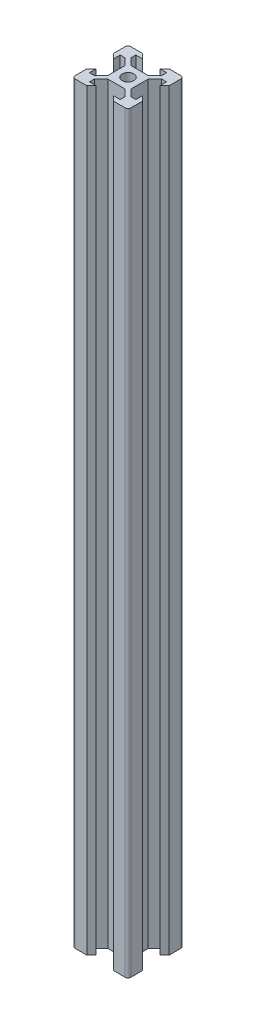
SolidWorks part; units mm, degrees
material "1060 Alloy"
ref_plane "Front Plane" through (0, 0, 0) normal (0, 0, 1) x (1, 0, 0)
ref_plane "Top Plane" through (0, 0, 0) normal (0, 1, 0) x (1, 0, 0)
ref_plane "Right Plane" through (0, 0, 0) normal (1, 0, 0) x (0, 0, -1)
ref_plane "End Plane" through (0, 270, 0) normal (0, 1, 0) x (1, 0, 0)
sketch "MasterLayoutSketch" plane through (0, 0, 0) normal (0, 1, 0) x (1, 0, 0)
  line L0 (-8.325, 3.1) -> (-8.325, 5.5)
  line L1 (-10, -10) -> (10, -10) construction
  line L2 (-10, -10) -> (-10, 10) construction
  line L3 (-10, 10) -> (10, 10) construction
  line L4 (10, -10) -> (10, 10) construction
  line L5 (-10, -10) -> (10, 10) construction
  line L6 (-10, 10) -> (10, -10) construction
  line L7 (-4.775, 10) -> (-3.1, 8.325)
  line L10 (-8.325, 5.5) -> (-6.5607, 5.5)
  line L11 (-10, 4.775) -> (-8.325, 3.1)
  line L12 (-5.5, 8.325) -> (-5.5, 6.5607)
  line L13 (-3.1, 8.325) -> (-5.5, 8.325)
  line L14 (-10, 10) -> (-10, 4.775)
  line L19 (3.1, 8.325) -> (5.5, 8.325)
  line L20 (10, 4.775) -> (8.325, 3.1)
  line L21 (-10, 10) -> (-4.775, 10)
  line L22 (-6.5607, 5.5) -> (-4.1607, 3.1)
  line L23 (-5.5, 6.5607) -> (-3.1, 4.1607)
  line L24 (5.5, 8.325) -> (5.5, 6.5607)
  line L25 (4.775, 10) -> (3.1, 8.325)
  line L26 (8.325, 5.5) -> (6.5607, 5.5)
  line L27 (8.325, 3.1) -> (8.325, 5.5)
  line L28 (10, 10) -> (4.775, 10)
  line L29 (10, 10) -> (10, 4.775)
  line L30 (5.5, 6.5607) -> (3.1, 4.1607)
  line L31 (6.5607, 5.5) -> (4.1607, 3.1)
  line L32 (8.325, -3.1) -> (8.325, -5.5)
  line L33 (4.775, -10) -> (3.1, -8.325)
  line L34 (8.325, -5.5) -> (6.5607, -5.5)
  line L35 (10, -4.775) -> (8.325, -3.1)
  line L36 (5.5, -8.325) -> (5.5, -6.5607)
  line L37 (3.1, -8.325) -> (5.5, -8.325)
  line L38 (10, -10) -> (10, -4.775)
  line L39 (10, -10) -> (4.775, -10)
  line L40 (6.5607, -5.5) -> (4.1607, -3.1)
  line L41 (5.5, -6.5607) -> (3.1, -4.1607)
  line L42 (-3.1, -8.325) -> (-5.5, -8.325)
  line L43 (-10, -4.775) -> (-8.325, -3.1)
  line L44 (-5.5, -8.325) -> (-5.5, -6.5607)
  line L45 (-4.775, -10) -> (-3.1, -8.325)
  line L46 (-8.325, -5.5) -> (-6.5607, -5.5)
  line L47 (-8.325, -3.1) -> (-8.325, -5.5)
  line L48 (-10, -10) -> (-4.775, -10)
  line L49 (-10, -10) -> (-10, -4.775)
  line L50 (-5.5, -6.5607) -> (-3.1, -4.1607)
  line L51 (-6.5607, -5.5) -> (-4.1607, -3.1)
  line L52 (-4.1607, 3.1) -> (-4.1607, -3.1)
  line L53 (-3.1, -4.1607) -> (3.1, -4.1607)
  line L54 (4.1607, -3.1) -> (4.1607, 3.1)
  line L55 (-3.1, 4.1607) -> (3.1, 4.1607)
  circle A0 centre (0, 0) radius 2.1
  point P0 (0, 0)
  point P9 (0, 0)
  dimension "D6" = 4.2
  dimension "D1" = 20
  dimension "D2" = 4
  dimension "D3" = 11
  dimension "D4" = 9.55
  dimension "D5" = 6.2
  dimension "D7" = 1.5
extrude "Main Extrusion" add sketch "MasterLayoutSketch" along normal up to surface (270 mm away) up to plane "End Plane"
fillet "Edge Fillets" radius 1 4 edges at (10, 135, -10) (10, 135, 10) (-10, 135, 10) (-10, 135, -10)
